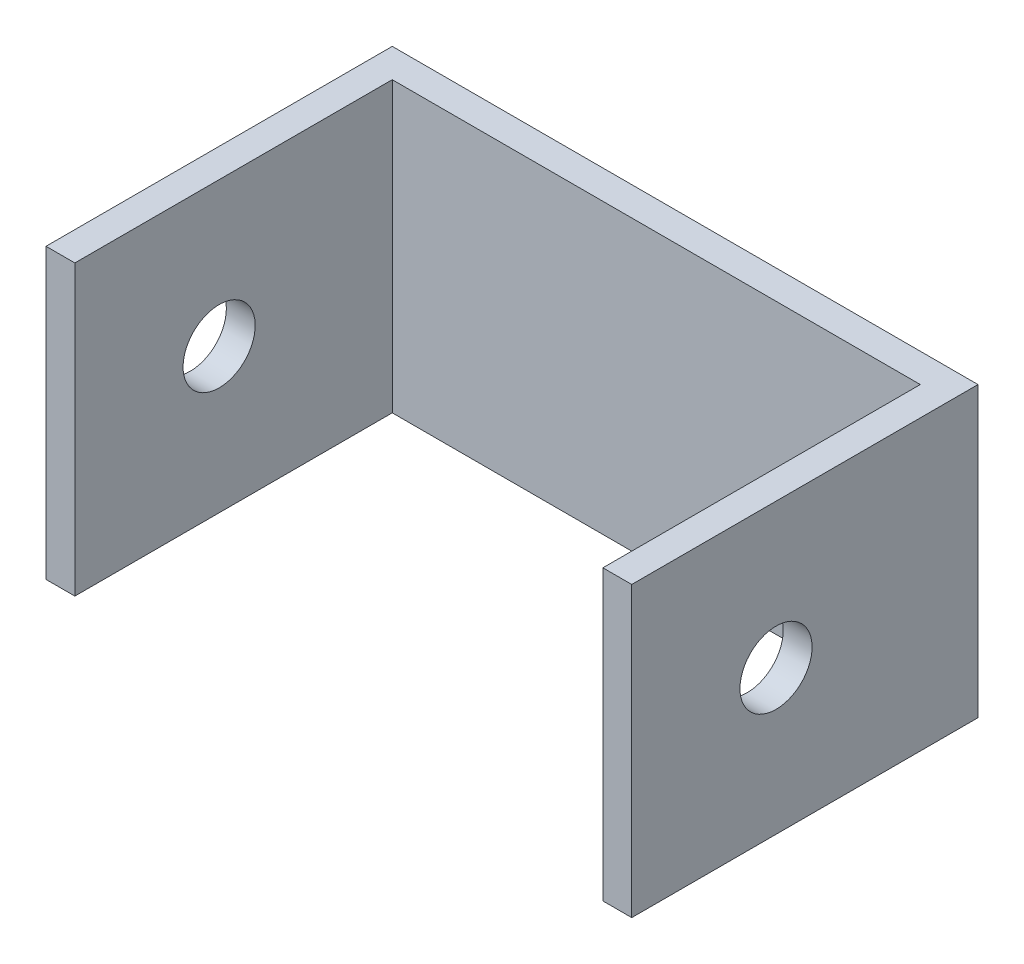
SolidWorks part; units mm, degrees
ref_plane "前视基准面" through (0, 0, 0) normal (0, 0, 1) x (1, 0, 0)
ref_plane "上视基准面" through (0, 0, 0) normal (0, 1, 0) x (1, 0, 0)
ref_plane "右视基准面" through (0, 0, 0) normal (1, 0, 0) x (0, 0, -1)
sketch "草图1" plane through (0, 0, 0) normal (0, 0, 1) x (1, 0, 0)
  line L1 (-20.3, 10) -> (20.3, 10)
  line L2 (-20.3, 10) -> (-20.3, -10)
  line L3 (-20.3, -10) -> (20.3, -10)
  line L4 (20.3, 10) -> (20.3, -10)
  line L5 (-20.3, 10) -> (20.3, -10) construction
  line L6 (-20.3, -10) -> (20.3, 10) construction
  point P0 (0, 0)
  dimension "D1" = 20
  dimension "D2" = 40.6
extrude "凸台-拉伸1" add sketch "草图1" along normal blind 2
sketch "草图2" plane through (0, 0, 2) normal (0, 0, 1) x (1, 0, 0)
  line L0 (-20.3, -10) -> (20.3, -10) construction
  line L1 (-20.3, 10) -> (-18.3, 10)
  line L2 (-20.3, 10) -> (-20.3, -10)
  line L3 (-20.3, -10) -> (-18.3, -10)
  line L4 (-18.3, 10) -> (-18.3, -10)
  line L6 (20.3, 10) -> (18.3, 10)
  line L7 (20.3, 10) -> (20.3, -10)
  line L8 (20.3, -10) -> (18.3, -10)
  line L9 (18.3, 10) -> (18.3, -10)
  dimension "D1" = 2
  dimension "D2" = 2
extrude "凸台-拉伸2" add sketch "草图2" along normal blind 22
sketch "草图3" plane through (-20.3, 0, 0) normal (-1, 0, 0) x (0, 0, 1)
  line L0 (-3.1876, 0) -> (25.8316, 0) construction
  line L1 (0, 12.9211) -> (0, -13.541) construction
  circle A1 centre (14, 0) radius 7 construction
  circle A2 centre (14, 0) radius 2.5
  dimension "D1" = 5
  dimension "D3" = 14
  dimension "D2" = 14
extrude "切除-拉伸1" cut sketch "草图3" against normal through all
